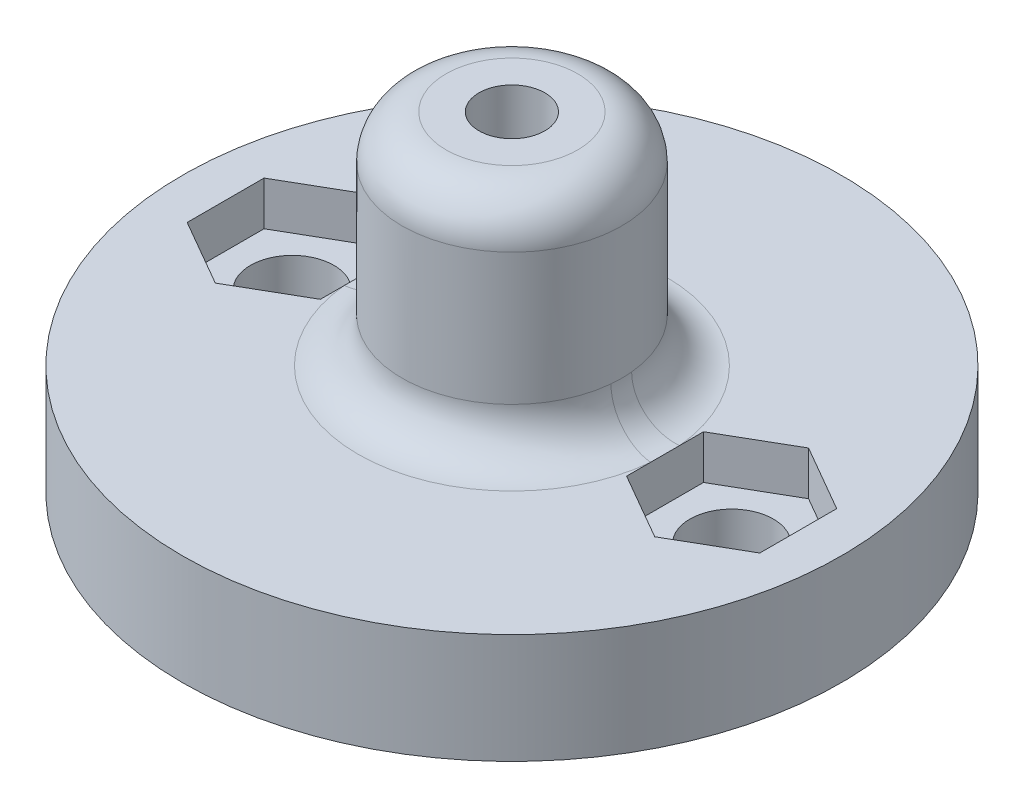
SolidWorks part; units mm, degrees
ref_plane "Спереди" through (0, 0, 0) normal (0, 0, 1) x (1, 0, 0)
ref_plane "Сверху" through (0, 0, 0) normal (0, 1, 0) x (1, 0, 0)
ref_plane "Справа" through (0, 0, 0) normal (1, 0, 0) x (0, 0, -1)
sketch "Эскиз1" plane through (0, 0, 0) normal (0, 1, 0) x (1, 0, 0)
  circle A0 centre (0, 0) radius 15
  dimension "D1" = 30
extrude "Бобышка-Вытянуть1" add sketch "Эскиз1" along normal blind 5
sketch "Эскиз2" plane through (0, 5, 0) normal (0, 1, 0) x (1, 0, 0)
  circle A0 centre (-10, 0) radius 1.9
  circle A1 centre (10, 0) radius 1.9
  dimension "D1" = 3.8
  dimension "D2" = 20
  dimension "D3" = 10
extrude "Вырез-Вытянуть1" cut sketch "Эскиз2" against normal blind 5
sketch "Эскиз3" plane through (0, 5, 0) normal (0, 1, 0) x (1, 0, 0)
  line L1 (-10, -3.5) -> (-6.9689, -1.75)
  line L2 (-6.9689, -1.75) -> (-6.9689, 1.75)
  line L3 (-6.9689, 1.75) -> (-10, 3.5)
  line L4 (-10, 3.5) -> (-13.0311, 1.75)
  line L5 (-13.0311, 1.75) -> (-13.0311, -1.75)
  line L6 (-13.0311, -1.75) -> (-10, -3.5)
  line L7 (10, -3.5) -> (13.0311, -1.75)
  line L8 (13.0311, -1.75) -> (13.0311, 1.75)
  line L9 (13.0311, 1.75) -> (10, 3.5)
  line L10 (10, 3.5) -> (6.9689, 1.75)
  line L11 (6.9689, 1.75) -> (6.9689, -1.75)
  line L12 (6.9689, -1.75) -> (10, -3.5)
  circle A0 centre (-10, 0) radius 3.5 construction
  circle A1 centre (10, 0) radius 3.5 construction
  circle A2 centre (10, 0) radius 1.9 construction
  circle A3 centre (-10, 0) radius 1.9 construction
  dimension "D1" = 7
extrude "Вырез-Вытянуть2" cut sketch "Эскиз3" against normal blind 2
sketch "Эскиз4" plane through (0, 5, 0) normal (0, 1, 0) x (1, 0, 0)
  circle A0 centre (0, 0) radius 5
  dimension "D1" = 10
extrude "Бобышка-Вытянуть2" add sketch "Эскиз4" along normal blind 10
fillet "Скругление1" radius 2 2 edges at (0, 15, 5) (0, 5, 5)
sketch "Эскиз5" plane through (0, 0, 0) normal (0, -1, 0) x (1, 0, 0)
  circle A0 centre (0, 0) radius 1.5
  dimension "D1" = 3
extrude "Вырез-Вытянуть3" cut sketch "Эскиз5" against normal blind 15
sketch "Эскиз6" plane through (0, 0, 0) normal (0, -1, 0) x (1, 0, 0)
  line L1 (0, 3.5) -> (-3.0311, 1.75)
  line L2 (-3.0311, 1.75) -> (-3.0311, -1.75)
  line L3 (-3.0311, -1.75) -> (0, -3.5)
  line L4 (0, -3.5) -> (3.0311, -1.75)
  line L5 (3.0311, -1.75) -> (3.0311, 1.75)
  line L6 (3.0311, 1.75) -> (0, 3.5)
  circle A0 centre (0, 0) radius 3.5 construction
  dimension "D1" = 7
extrude "Вырез-Вытянуть4" cut sketch "Эскиз6" against normal blind 2.7
